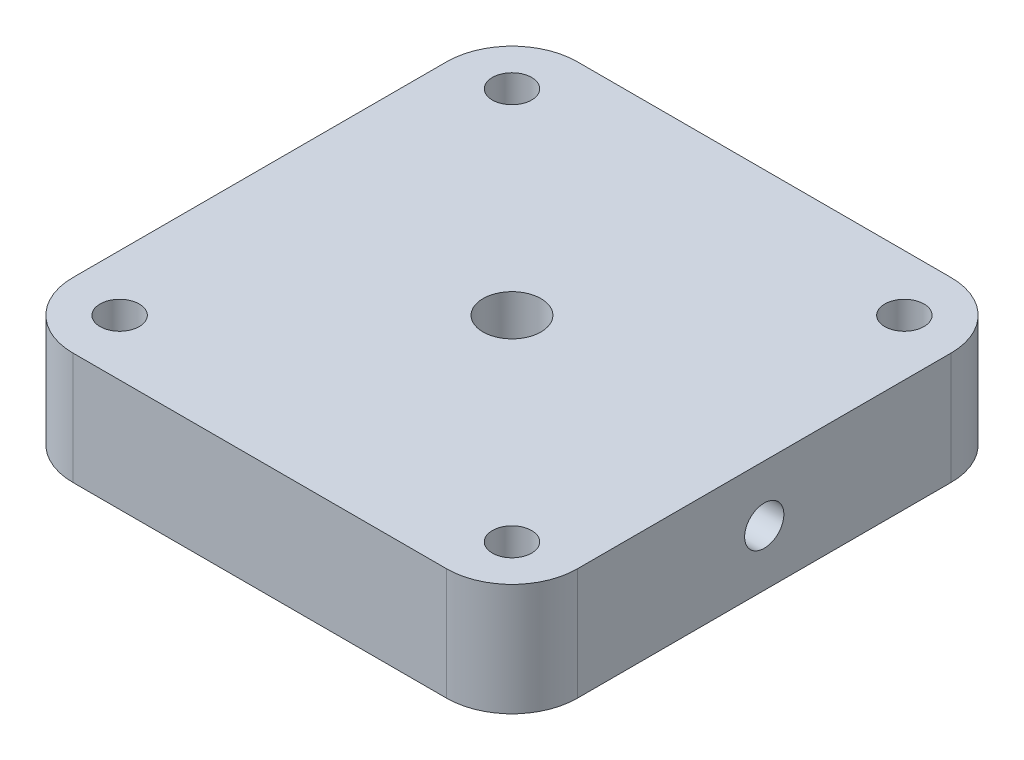
SolidWorks part; units mm, degrees
ref_plane "正面" through (0, 0, 0) normal (0, 0, 1) x (1, 0, 0)
ref_plane "平面" through (0, 0, 0) normal (0, 1, 0) x (1, 0, 0)
ref_plane "右側面" through (0, 0, 0) normal (1, 0, 0) x (0, 0, -1)
sketch "ｽｹｯﾁ1" plane through (0, 0, 0) normal (0, 1, 0) x (1, 0, 0)
  line L1 (-10, 13.5) -> (10, 13.5)
  line L2 (-13.5, 10) -> (-13.5, -10)
  line L3 (-10, -13.5) -> (10, -13.5)
  line L4 (13.5, 10) -> (13.5, -10)
  line L5 (-13.5, 13.5) -> (13.5, -13.5) construction
  line L6 (-13.5, -13.5) -> (13.5, 13.5) construction
  circle A0 centre (0, 0) radius 1.55
  arc A1 (-13.5, -10) -> (-10, -13.5) centre (-10, -10) ccw
  arc A2 (10, -13.5) -> (13.5, -10) centre (10, -10) ccw
  arc A3 (13.5, 10) -> (10, 13.5) centre (10, 10) ccw
  arc A4 (-10, 13.5) -> (-13.5, 10) centre (-10, 10) ccw
  circle A5 centre (-10.5, -10.5) radius 1.05
  circle A7 centre (10.5, -10.5) radius 1.05
  circle A8 centre (10.5, 10.5) radius 1.05
  circle A9 centre (-10.5, 10.5) radius 1.05
  point P0 (0, 0)
  dimension "D3" = 3.1
  dimension "D4" = 3.5
  dimension "D5" = 3
  dimension "D6" = 3
  dimension "D7" = 3
  dimension "D8" = 21
  dimension "D9" = 2.1
  dimension "D10" = 2.1
  dimension "D11" = 2.1
  dimension "D12" = 2.1
  dimension "D13" = 21
  dimension "D14" = 21
  dimension "D15" = 21
  dimension "D16" = 3
  dimension "D1" = 27
  dimension "D2" = 27
extrude "ﾎﾞｽ - 押し出し1" add sketch "ｽｹｯﾁ1" along normal blind 6
sketch "ｽｹｯﾁ2" plane through (13.5, 0, 0) normal (1, 0, 0) x (0, 0, -1)
  line L0 (-10, 6) -> (-10, 0) construction
  line L1 (-10, 6) -> (10, 6) construction
  circle A0 centre (0, 3) radius 1.05
  dimension "D1" = 2.1
  dimension "D2" = 10
  dimension "D3" = 3
extrude "ｶｯﾄ - 押し出し1" cut sketch "ｽｹｯﾁ2" against normal through all
sketch "ｽｹｯﾁ3" plane through (0, 0, 0) normal (0, -1, 0) x (1, 0, 0)
  circle A0 centre (0, 0) radius 4
extrude "ｶｯﾄ - 押し出し2" cut sketch "ｽｹｯﾁ3" against normal blind 3
